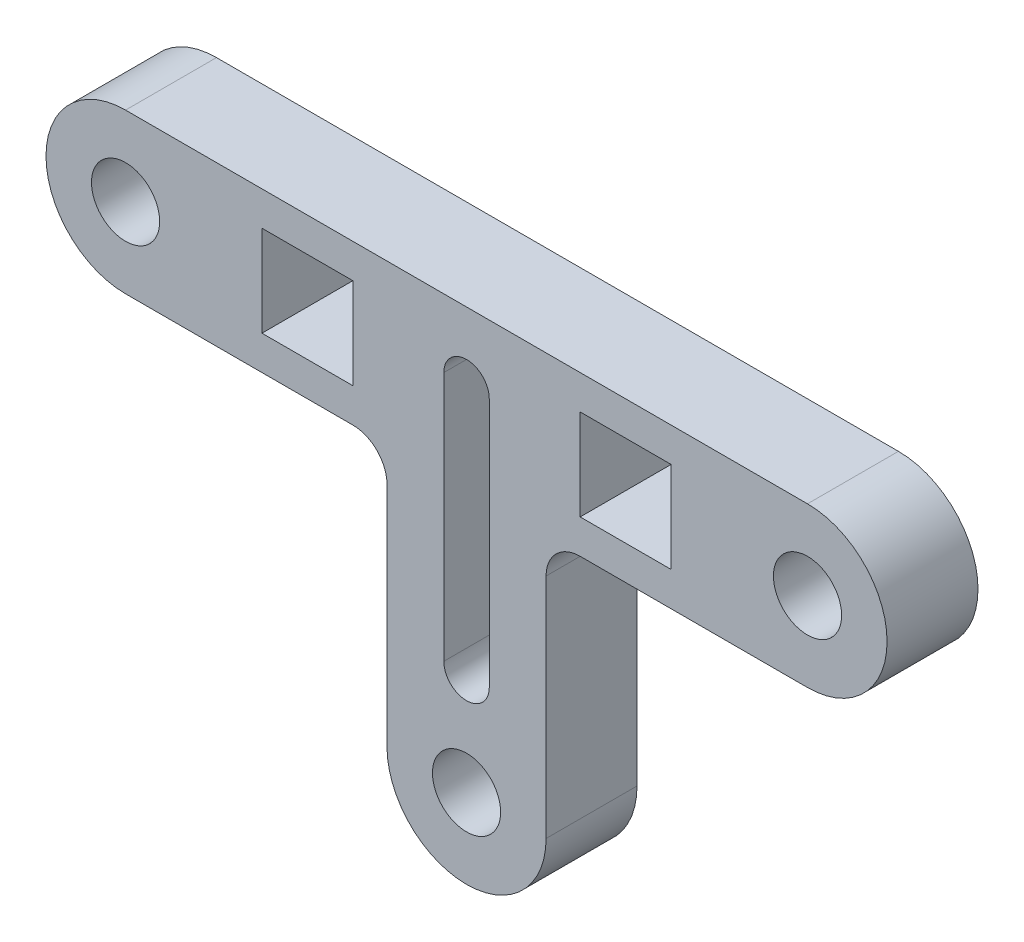
SolidWorks part; units mm, degrees
ref_plane "Plan de face" through (0, 0, 0) normal (0, 0, 1) x (1, 0, 0)
ref_plane "Plan de dessus" through (0, 0, 0) normal (0, 1, 0) x (1, 0, 0)
ref_plane "Plan de droite" through (0, 0, 0) normal (1, 0, 0) x (0, 0, -1)
sketch "Esquisse1" plane through (0, 0, 0) normal (0, 0, 1) x (1, 0, 0)
  line L0 (-3.5, 0) -> (-3.5, 10)
  line L1 (-5, 11.5) -> (-15, 11.5)
  line L2 (-15, 18.5) -> (15, 18.5)
  line L3 (0, 0) -> (0, 13.606) construction
  line L4 (15, 11.5) -> (5, 11.5)
  line L5 (3.5, 0) -> (3.5, 10)
  line L7 (-5, 17) -> (-9, 17)
  line L8 (-5, 17) -> (-5, 13)
  line L9 (-5, 13) -> (-9, 13)
  line L10 (-9, 17) -> (-9, 13)
  line L11 (-5, 17) -> (-9, 13) construction
  line L12 (-5, 13) -> (-9, 17) construction
  line L13 (9, 17) -> (5, 17)
  line L14 (9, 17) -> (9, 13)
  line L15 (9, 13) -> (5, 13)
  line L16 (5, 17) -> (5, 13)
  line L17 (9, 17) -> (5, 13) construction
  line L18 (9, 13) -> (5, 17) construction
  arc A0 (3.5, 0) -> (-3.5, 0) centre (0, 0) cw
  arc A1 (-3.5, 10) -> (-5, 11.5) centre (-5, 10) ccw
  arc A2 (-15, 11.5) -> (-15, 18.5) centre (-15, 15) cw
  arc A3 (15, 18.5) -> (15, 11.5) centre (15, 15) cw
  arc A4 (5, 11.5) -> (3.5, 10) centre (5, 10) ccw
  circle A5 centre (0, 0) radius 1.5
  circle A6 centre (-15, 15) radius 1.5
  circle A7 centre (15, 15) radius 1.5
  point P19 (-7, 15)
  point P24 (7, 15)
  dimension "D1" = 3
  dimension "D6" = 3.5
  dimension "D5" = 1.5
  dimension "D2" = 30
  dimension "D3" = 15
  dimension "D4" = 4
extrude "Boss.-Extru.1" add sketch "Esquisse1" along normal blind 4
sketch "Esquisse2" plane through (0, 0, 4) normal (0, 0, 1) x (1, 0, 0)
  line L0 (0, 4.5) -> (0, 15.5) construction
  line L1 (-1, 4.5) -> (-1, 15.5)
  line L2 (1, 4.5) -> (1, 15.5)
  line L3 (15, 18.5) -> (-15, 18.5) construction
  line L4 (0, 16.5) -> (0, 18.5) construction
  line L5 (0, 1.5) -> (0, 3.5) construction
  arc A0 (-1, 4.5) -> (1, 4.5) centre (0, 4.5) ccw
  arc A1 (1, 15.5) -> (-1, 15.5) centre (0, 15.5) ccw
  circle A2 centre (0, 0) radius 1.5 construction
  point P3 (0, 10)
  point P8 (0, 3.5)
  point P9 (0, 16.5)
  point P10 (0, 1.5)
  point P11 (0, 18.5)
  dimension "D1" = 2
  dimension "D2" = 2
extrude "Enlèv. mat.-Extru.1" cut sketch "Esquisse2" against normal up to next
